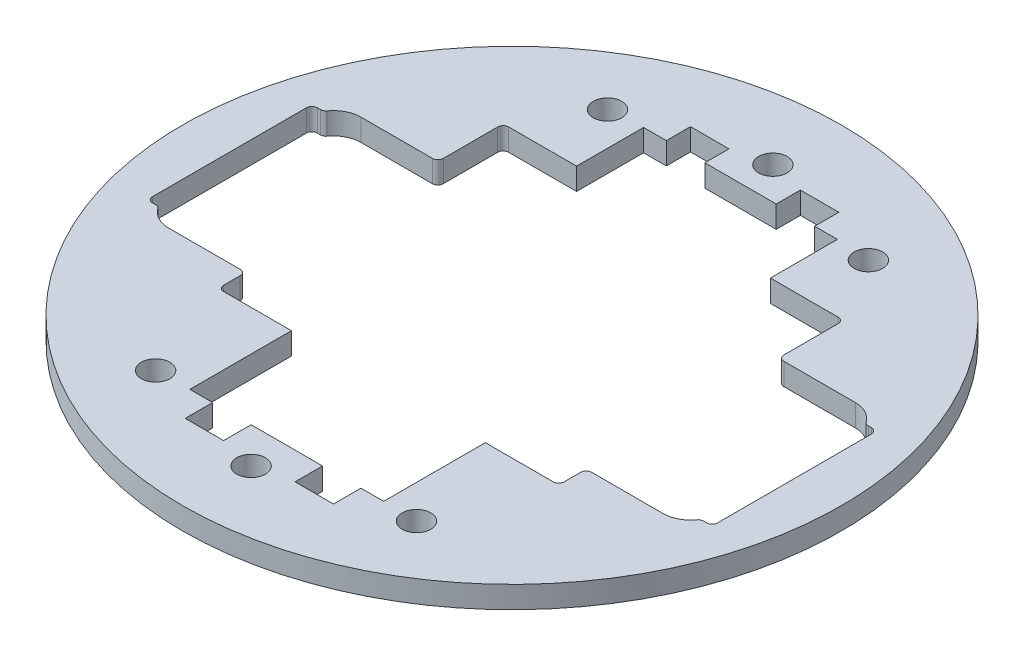
SolidWorks part; units mm, degrees
material "1060 合金"
ref_plane "前视基准面" through (0, 0, 0) normal (0, 0, 1) x (1, 0, 0)
ref_plane "上视基准面" through (0, 0, 0) normal (0, 1, 0) x (1, 0, 0)
ref_plane "右视基准面" through (0, 0, 0) normal (1, 0, 0) x (0, 0, -1)
sketch "草图1" plane through (0, 0, 0) normal (0, 1, 0) x (1, 0, 0)
  circle A0 centre (0, 0) radius 54.5
  dimension "D1" = 109
extrude "凸台-拉伸1" add sketch "草图1" along normal blind 4
sketch "草图2" plane through (0, 4, 0) normal (0, 1, 0) x (1, 0, 0)
  line L1 (-50, 17.5) -> (50, 17.5)
  line L2 (-50, 17.5) -> (-50, -17.5)
  line L3 (-50, -17.5) -> (50, -17.5)
  line L4 (50, 17.5) -> (50, -17.5)
  line L5 (-50, 17.5) -> (50, -17.5) construction
  line L6 (-50, -17.5) -> (50, 17.5) construction
  point P0 (0, 0)
  dimension "D1" = 100
  dimension "D2" = 35
extrude "切除-拉伸1" cut sketch "草图2" against normal blind 4
fillet "圆角1" radius 5 4 edges at (-50, 2, 17.5) (50, 2, -17.5) (50, 2, 17.5) (-50, 2, -17.5)
sketch "草图3" plane through (0, 0, 0) normal (0, -1, 0) x (1, 0, 0)
  line L0 (0, 0) -> (-23.75, 41.1362)
  line L1 (-23.75, 41.1362) -> (23.75, 41.1362)
  line L2 (23.75, 41.1362) -> (-0.5837, -1.011)
  circle A0 centre (0, 0) radius 47.5
  circle A2 centre (-23.75, 41.1362) radius 2.6
  circle A3 centre (23.75, 41.1362) radius 2.6
  circle A4 centre (0, 47.5) radius 2.6
  dimension "D1" = 95
  dimension "D2" = 60
  dimension "D3" = 5.2
  dimension "D4" = 5.2
  dimension "D5" = 5.2
extrude "切除-拉伸2" cut sketch "草图3" against normal blind 10 contours A0 A2 L0 | A0 A2 | L0 A2 L1 | L1 A2 A0 | A0 A4 | A0 A4 | L1 A3 L2 | L2 A3 A0 | A0 A3 L1 | A0 A3
pattern_circular "阵列(圆周)1" count 2 over 360 about axis through (0, 0, 0) along (0, 1, 0) of "切除-拉伸2"
sketch "草图4" plane through (0, 0, 0) normal (0, -1, 0) x (1, 0, 0)
  line L0 (-15, 29.5) -> (15, 29.5)
  line L1 (0, 0) -> (0, 29.5)
  line L2 (-45, 17.5) -> (45, 17.5) construction
  circle A0 centre (-15, 29.5) radius 2.6
  circle A1 centre (15, 29.5) radius 2.6
  dimension "D3" = 5.2
  dimension "D4" = 5.2
  dimension "D1" = 30
  dimension "D2" = 90
  dimension "D5" = 12
extrude "切除-拉伸3" cut sketch "草图4" against normal blind 10
sketch "草图5" plane through (0, 0, 0) normal (0, -1, 0) x (1, 0, 0)
  line L0 (0, 0) -> (0, -33.5)
  line L1 (-15, -33.5) -> (15, -33.5)
  line L2 (45, -17.5) -> (-45, -17.5) construction
  circle A0 centre (-15, -33.5) radius 2.6
  circle A1 centre (15, -33.5) radius 2.6
  point P6 (0, -33.5)
  dimension "D3" = 5.2
  dimension "D4" = 5.2
  dimension "D1" = 16
  dimension "D2" = 30
extrude "切除-拉伸4" cut sketch "草图5" against normal blind 100
sketch "草图6" plane through (0, 0, 0) normal (0, -1, 0) x (1, 0, 0)
  line L0 (-45, 17.5) -> (45, 17.5) construction
  line L1 (17.65, -37) -> (-17.65, -37)
  line L2 (17.65, -37) -> (17.65, 37)
  line L3 (17.65, 37) -> (-17.65, 37)
  line L4 (-17.65, -37) -> (-17.65, 37)
  line L5 (17.65, -37) -> (-17.65, 37) construction
  line L6 (17.65, 37) -> (-17.65, -37) construction
  line L8 (-17.65, -37) -> (17.65, -37)
  line L9 (-17.65, -37) -> (-17.65, -38.5)
  line L10 (-17.65, -38.5) -> (17.65, -38.5)
  line L11 (17.65, -37) -> (17.65, -38.5)
  point P0 (0, 0)
  circle M6 centre (-15, -33.5) radius 2.6
  circle M7 centre (15, -33.5) radius 2.6
  circle M8 centre (-15, 29.5) radius 2.6
  circle M9 centre (15, 29.5) radius 2.6
  line M18 (-45, 17.5) -> (45, 17.5)
  line M22 (45, -17.5) -> (-45, -17.5)
  dimension "D1" = 19.5
  dimension "D2" = 35.3
  dimension "D3" = 1.5
extrude "切除-拉伸5" cut sketch "草图6" against normal blind 10 contours L4 L1 L2 M22 M6 M7 | L11 L1 L9 L10 | L4 L2 L3 M18 M9 M8
sketch "草图7" plane through (0, 0, 0) normal (0, -1, 0) x (1, 0, 0)
  line L0 (17.65, 17.5) -> (45, 17.5) construction
  line L1 (-31, 22.5) -> (31, 22.5)
  line L2 (-31, 22.5) -> (-31, -22.5)
  line L4 (31, 22.5) -> (31, -22.5)
  line L5 (-31, 22.5) -> (31, -22.5) construction
  line L6 (-31, -22.5) -> (31, 22.5) construction
  line L9 (-31, -22.5) -> (-31, -29.4)
  line L10 (-31, -29.4) -> (31, -29.4)
  line L11 (31, -22.5) -> (31, -29.4)
  point P0 (0, 0)
  dimension "D1" = 5
  dimension "D2" = 62
  dimension "D3" = 6.9
extrude "切除-拉伸6" cut sketch "草图7" against normal blind 10
sketch "草图8" plane through (0, 0, 0) normal (0, -1, 0) x (1, 0, 0)
  line L0 (17.65, -38.5) -> (17.65, -29.4) construction
  line L1 (-17.65, -38.5) -> (17.65, -38.5)
  line L2 (-17.65, -38.5) -> (-17.65, -41.6)
  line L3 (-17.65, -41.6) -> (17.65, -41.6)
  line L4 (17.65, -38.5) -> (17.65, -41.6)
  dimension "D1" = 3.1
  dimension "D2" = 0
sketch "草图9" plane through (0, 0, 0) normal (0, -1, 0) x (-1, 0, 0)
  circle A0 centre (23.75, 41.1362) radius 3.96
  circle A1 centre (0, 47.5) radius 3.96
  dimension "D1" = 7.92
  dimension "D2" = 7.92
fillet "圆角2" radius 1 8 edges at (-31, 2, -29.4) (-31, 2, -17.5) (31, 2, 22.5) (31, 2, 17.5) (31, 2, -17.5) (31, 2, -29.4) (-31, 2, 22.5) (-31, 2, 17.5)
extrude "切除-拉伸7" cut sketch "草图8" against normal blind 10
sketch "草图10" plane through (0, 0, 0) normal (0, -1, 0) x (1, 0, 0)
  line L0 (17.65, 22.5) -> (17.65, 37) construction
  line L1 (-17.65, 37) -> (17.65, 37)
  line L2 (-17.65, 37) -> (-17.65, 41)
  line L3 (-17.65, 41) -> (17.65, 41)
  line L4 (17.65, 37) -> (17.65, 41)
  dimension "D1" = 0
  dimension "D2" = 4
extrude "切除-拉伸8" cut sketch "草图10" against normal blind 54.5
sketch "草图11" plane through (0, 0, 0) normal (0, -1, 0) x (1, 0, 0)
  circle A0 centre (0, 0) radius 56.5
  circle A1 centre (0, 0) radius 54.5 construction
  circle A2 centre (0, 0) radius 54.5
  dimension "D1" = 2
extrude "凸台-拉伸2" add sketch "草图11" against normal up to surface (4 mm away) up to face at (0, 4, -1.3312)
sketch "草图12" plane through (0, 0, 0) normal (0, -1, 0) x (1, 0, 0)
  line L0 (17.65, 41) -> (-17.65, 41) construction
  line L1 (10, -46) -> (-10, -46)
  line L2 (10, -46) -> (10, 46)
  line L3 (10, 46) -> (-10, 46)
  line L4 (-10, -46) -> (-10, 46)
  line L5 (10, -46) -> (-10, 46) construction
  line L6 (10, 46) -> (-10, -46) construction
  line L8 (-6.5, 36) -> (-13.5, 36)
  line L9 (-6.5, 36) -> (-6.5, 46)
  line L10 (-6.5, 46) -> (-13.5, 46)
  line L11 (-13.5, 36) -> (-13.5, 46)
  line L12 (-6.5, 36) -> (-13.5, 46) construction
  line L13 (-6.5, 46) -> (-13.5, 36) construction
  line L14 (6.5, 36) -> (13.5, 36)
  line L15 (6.5, 36) -> (6.5, 46)
  line L16 (6.5, 46) -> (13.5, 46)
  line L17 (13.5, 36) -> (13.5, 46)
  line L18 (6.5, 36) -> (13.5, 46) construction
  line L19 (6.5, 46) -> (13.5, 36) construction
  point P0 (0, 0)
  point P8 (-10, 41)
  point P13 (10, 41)
  line M11 (-17.65, 41) -> (17.65, 41)
  dimension "D1" = 5
  dimension "D2" = 20
  dimension "D3" = 7
  dimension "D4" = 7
extrude "切除-拉伸9" cut sketch "草图12" against normal blind 6 contours L9 L3 L4 M11 | L11 L4 L10 M11 | L15 L2 L3 M11 | L17 L16 L2 M11
pattern_circular "阵列(圆周)2" count 2 over 360 about axis through (0, 0, 0) along (0, 1, 0) of "切除-拉伸9"
sketch "草图13" plane through (0, 0, 0) normal (0, -1, 0) x (1, 0, 0)
  line L36 (13.5, -46) -> (13.5, -41.6)
  line L37 (6.5, -46) -> (13.5, -46)
  line L38 (6.5, -41.6) -> (6.5, -46)
  line L39 (-6.5, -41.6) -> (6.5, -41.6)
  line L40 (-6.5, -46) -> (-6.5, -41.6)
  line L41 (-13.5, -46) -> (-6.5, -46)
  line L42 (-13.5, -41.6) -> (-13.5, -46)
  line L43 (-17.65, -41.6) -> (-13.5, -41.6)
  line L44 (-17.65, -29.4) -> (-17.65, -41.6)
  line L45 (-30, -29.4) -> (-17.65, -29.4)
  line L46 (-31, -18.5) -> (-31, -28.4)
  line L47 (-45, -17.5) -> (-32, -17.5)
  line L48 (-50, 12.5) -> (-50, -12.5)
  line L49 (-32, 17.5) -> (-45, 17.5)
  line L50 (-31, 21.5) -> (-31, 18.5)
  line L51 (-17.65, 22.5) -> (-30, 22.5)
  line L52 (-17.65, 41) -> (-17.65, 22.5)
  line L53 (-13.5, 41) -> (-17.65, 41)
  line L54 (-13.5, 46) -> (-13.5, 41)
  line L55 (-6.5, 46) -> (-13.5, 46)
  line L56 (-6.5, 41) -> (-6.5, 46)
  line L57 (6.5, 41) -> (-6.5, 41)
  line L58 (6.5, 46) -> (6.5, 41)
  line L59 (13.5, 46) -> (6.5, 46)
  line L60 (13.5, 41) -> (13.5, 46)
  line L61 (17.65, 41) -> (13.5, 41)
  line L62 (17.65, 22.5) -> (17.65, 41)
  line L63 (30, 22.5) -> (17.65, 22.5)
  line L64 (31, 18.5) -> (31, 21.5)
  line L65 (45, 17.5) -> (32, 17.5)
  line L66 (50, -12.5) -> (50, 12.5)
  line L67 (32, -17.5) -> (45, -17.5)
  line L68 (31, -28.4) -> (31, -18.5)
  line L69 (17.65, -29.4) -> (30, -29.4)
  line L70 (17.65, -41.6) -> (17.65, -29.4)
  line L71 (13.5, -41.6) -> (17.65, -41.6)
  line L72 (13.5, -46) -> (13.5, -41.6)
  line L73 (6.5, -46) -> (13.5, -46)
  line L74 (6.5, -41.6) -> (6.5, -46)
  line L75 (-6.5, -41.6) -> (6.5, -41.6)
  line L76 (-6.5, -46) -> (-6.5, -41.6)
  line L77 (-13.5, -46) -> (-6.5, -46)
  line L78 (-13.5, -41.6) -> (-13.5, -46)
  line L79 (-17.65, -41.6) -> (-13.5, -41.6)
  line L80 (-17.65, -29.4) -> (-17.65, -41.6)
  line L81 (-30, -29.4) -> (-17.65, -29.4)
  line L82 (-31, -18.5) -> (-31, -28.4)
  line L83 (-45, -17.5) -> (-32, -17.5)
  line L84 (-50, 12.5) -> (-50, -12.5)
  line L85 (-32, 17.5) -> (-45, 17.5)
  line L86 (-31, 21.5) -> (-31, 18.5)
  line L87 (-17.65, 22.5) -> (-30, 22.5)
  line L88 (-17.65, 41) -> (-17.65, 22.5)
  line L89 (-13.5, 41) -> (-17.65, 41)
  line L90 (-13.5, 46) -> (-13.5, 41)
  line L91 (-6.5, 46) -> (-13.5, 46)
  line L92 (-6.5, 41) -> (-6.5, 46)
  line L93 (6.5, 41) -> (-6.5, 41)
  line L94 (6.5, 46) -> (6.5, 41)
  line L95 (13.5, 46) -> (6.5, 46)
  line L96 (13.5, 41) -> (13.5, 46)
  line L97 (17.65, 41) -> (13.5, 41)
  line L98 (17.65, 22.5) -> (17.65, 41)
  line L99 (30, 22.5) -> (17.65, 22.5)
  line L100 (31, 18.5) -> (31, 21.5)
  line L101 (45, 17.5) -> (32, 17.5)
  line L102 (50, -12.5) -> (50, 12.5)
  line L103 (32, -17.5) -> (45, -17.5)
  line L104 (31, -28.4) -> (31, -18.5)
  line L105 (17.65, -29.4) -> (30, -29.4)
  line L106 (17.65, -41.6) -> (17.65, -29.4)
  line L107 (13.5, -41.6) -> (17.65, -41.6)
  circle A0 centre (23.75, 41.1362) radius 2.6 construction
  circle A1 centre (0, 0) radius 56.5
  circle A2 centre (0, 0) radius 56.5
  circle A3 centre (23.75, -41.1362) radius 2.6
  circle A4 centre (23.75, -41.1362) radius 2.6
  circle A5 centre (-23.75, -41.1362) radius 2.6
  circle A6 centre (-23.75, -41.1362) radius 2.6
  circle A7 centre (0, -47.5) radius 2.6
  circle A8 centre (0, -47.5) radius 2.6
  circle A9 centre (0, 47.5) radius 2.6 construction
  circle A10 centre (-23.75, 41.1362) radius 2.6 construction
  circle A11 centre (23.75, 41.1362) radius 2.6
  circle A12 centre (0, 47.5) radius 2.6
  circle A13 centre (-23.75, 41.1362) radius 2.6
  arc A20 (-31, -28.4) -> (-30, -29.4) centre (-30, -28.4) ccw
  arc A21 (-31, -18.5) -> (-32, -17.5) centre (-32, -18.5) ccw
  arc A22 (-50, -12.5) -> (-45, -17.5) centre (-45, -12.5) ccw
  arc A23 (-45, 17.5) -> (-50, 12.5) centre (-45, 12.5) ccw
  arc A24 (-32, 17.5) -> (-31, 18.5) centre (-32, 18.5) ccw
  arc A25 (-30, 22.5) -> (-31, 21.5) centre (-30, 21.5) ccw
  arc A26 (31, 21.5) -> (30, 22.5) centre (30, 21.5) ccw
  arc A27 (31, 18.5) -> (32, 17.5) centre (32, 18.5) ccw
  arc A28 (50, 12.5) -> (45, 17.5) centre (45, 12.5) ccw
  arc A29 (45, -17.5) -> (50, -12.5) centre (45, -12.5) ccw
  arc A30 (32, -17.5) -> (31, -18.5) centre (32, -18.5) ccw
  arc A31 (30, -29.4) -> (31, -28.4) centre (30, -28.4) ccw
  arc A32 (-31, -28.4) -> (-30, -29.4) centre (-30, -28.4) ccw
  arc A33 (-31, -18.5) -> (-32, -17.5) centre (-32, -18.5) ccw
  arc A34 (-50, -12.5) -> (-45, -17.5) centre (-45, -12.5) ccw
  arc A35 (-45, 17.5) -> (-50, 12.5) centre (-45, 12.5) ccw
  arc A36 (-32, 17.5) -> (-31, 18.5) centre (-32, 18.5) ccw
  arc A37 (-30, 22.5) -> (-31, 21.5) centre (-30, 21.5) ccw
  arc A38 (31, 21.5) -> (30, 22.5) centre (30, 21.5) ccw
  arc A39 (31, 18.5) -> (32, 17.5) centre (32, 18.5) ccw
  arc A40 (50, 12.5) -> (45, 17.5) centre (45, 12.5) ccw
  arc A41 (45, -17.5) -> (50, -12.5) centre (45, -12.5) ccw
  arc A42 (32, -17.5) -> (31, -18.5) centre (32, -18.5) ccw
  arc A43 (30, -29.4) -> (31, -28.4) centre (30, -28.4) ccw
  dimension "D1" = 0
  dimension "D2" = 0
  dimension "D3" = 0
  dimension "D4" = 0
  dimension "D5" = 0
sketch "草图14" plane through (0, 0, 0) normal (0, -1, 0) x (-1, 0, 0)
  line L1 (-51.44, 15) -> (51.44, 15)
  line L2 (-51.44, 15) -> (-51.44, -15)
  line L3 (-51.44, -15) -> (51.44, -15)
  line L4 (51.44, 15) -> (51.44, -15)
  line L5 (-51.44, 15) -> (51.44, -15) construction
  line L6 (-51.44, -15) -> (51.44, 15) construction
  point P0 (0, 0)
  dimension "D1" = 102.88
  dimension "D2" = 30
extrude "切除-拉伸10" cut sketch "草图14" against normal blind 30
fillet "圆角3" radius 1 8 edges at (49.3301, 2, 15) (51.44, 2, 15) (51.44, 2, -15) (49.3301, 2, -15) (-51.44, 2, -15) (-49.3301, 2, -15) (-49.3301, 2, 15) (-51.44, 2, 15)
sketch "草图15" plane through (0, 0, 0) normal (0, -1, 0) x (1, 0, 0)
  circle A0 centre (0, 0) radius 56.5
  circle A1 centre (0, 0) radius 60
  dimension "D1" = 120
extrude "凸台-拉伸3" add sketch "草图15" against normal up to surface (4 mm away) up to face at (0, 4, -0.75)
